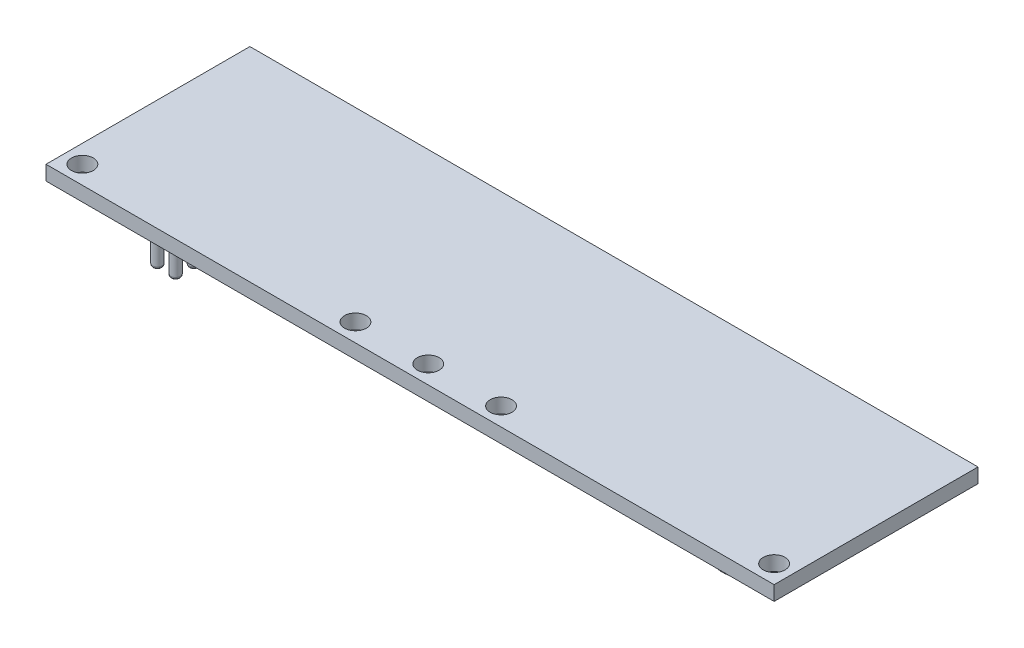
SolidWorks part; units mm, degrees
ref_plane "Front Plane" through (0, 0, 0) normal (0, 0, 1) x (1, 0, 0)
ref_plane "Top Plane" through (0, 0, 0) normal (0, 1, 0) x (1, 0, 0)
ref_plane "Right Plane" through (0, 0, 0) normal (1, 0, 0) x (0, 0, -1)
sketch "Sketch1" plane through (0, 0, 0) normal (0, 1, 0) x (1, 0, 0)
  line L0 (0, 0) -> (0, 28)
  line L1 (0, 28) -> (100, 28)
  line L2 (100, 28) -> (100, 0)
  line L3 (100, 0) -> (0, 0)
  dimension "D1" = 100
  dimension "D2" = 28
extrude "BOARD" add sketch "Sketch1" along normal blind 2
sketch "PICTURE" plane through (0, 2, 0) normal (0, 1, 0) x (1, 0, 0)
  line L0 (114.1667, 96.5) -> (570.8333, 96.5) construction
sketch "Sketch4" plane through (0, 0, 0) normal (0, 1, 0) x (1, 0, 0)
  line L0 (0, 28) -> (0, 0) construction
  line L1 (0, 0) -> (100, 0) construction
  line L2 (100, 0) -> (100, 28) construction
  circle A0 centre (2.5, 2.5) radius 1.5
  circle A1 centre (40, 2.5) radius 1.5
  circle A2 centre (50, 2.5) radius 1.5
  circle A3 centre (60, 2.5) radius 1.5
  circle A4 centre (97.5, 2.5) radius 1.5
  dimension "D1" = 3
  dimension "D4" = 10
  dimension "D6" = 10
  dimension "D2" = 2.5
  dimension "D3" = 2.5
  dimension "D5" = 37.5
  dimension "D7" = 2.5
extrude "SCREW HOLES" cut sketch "Sketch4" along normal through all and the other way through all
sketch "Sketch6" plane through (0, 0, 0) normal (0, -1, 0) x (1, 0, 0)
  line L0 (5, -7.5) -> (10, -7.5)
  line L1 (10, -7.5) -> (10, -15.5)
  line L2 (10, -15.5) -> (5, -15.5)
  line L3 (5, -15.5) -> (5, -7.5)
  line L4 (100, -28) -> (0, -28) construction
  line L5 (0, -28) -> (0, 0) construction
  dimension "D1" = 8
  dimension "D2" = 5
  dimension "D3" = 12.5
  dimension "D4" = 5
extrude "PIN BASE" add sketch "Sketch6" along normal blind 1.5 separate body
sketch "Sketch7" plane through (0, -1.5, 0) normal (0, -1, 0) x (1, 0, 0)
  line L0 (5, -7.5) -> (5, -15.5) construction
  line L1 (10, -7.5) -> (5, -7.5) construction
  circle A0 centre (6.3, -9) radius 0.65
  circle A1 centre (8.8, -9) radius 0.65
  circle A2 centre (8.8, -11.5) radius 0.65
  circle A3 centre (8.8, -14) radius 0.65
  circle A4 centre (6.3, -11.5) radius 0.65
  circle A5 centre (6.3, -14) radius 0.65
  dimension "D1" = 1.3
  dimension "D4" = 1.3
  dimension "D5" = 1.5
  dimension "D2" = 2
  dimension "D3" = 3
extrude "PINS" add sketch "Sketch7" along normal blind 10 separate body
fillet "Fillet1" radius 0.4 1 edges at (6.3, -11.5, -9.65)
fillet "Fillet2" radius 0.4 1 edges at (6.3, -11.5, -12.15)
fillet "Fillet3" radius 0.4 1 edges at (8.8, -11.5, -9.65)
fillet "Fillet4" radius 0.4 1 edges at (8.8, -11.5, -12.15)
fillet "Fillet5" radius 0.4 1 edges at (6.3, -11.5, -14.65)
fillet "Fillet6" radius 0.4 1 edges at (8.8, -11.5, -14.65)
sketch "Sketch8" plane through (0, 0, 0) normal (0, -1, 0) x (1, 0, 0)
  text T0 "GND           GND" font "Century Gothic" height in points 5
extrude "gnd" add sketch "Sketch8" along normal blind 0.1 separate body
sketch "Sketch9" plane through (0, 0, 0) normal (0, -1, 0) x (1, 0, 0)
  text T0 "5V            5V" font "Century Gothic" height in points 5
extrude "5v" add sketch "Sketch9" along normal blind 0.1 separate body
sketch "Sketch10" plane through (0, 0, 0) normal (0, -1, 0) x (1, 0, 0)
  text T0 "SCL           SDA" font "Century Gothic" height in points 5
extrude "SLC & SDA" add sketch "Sketch10" along normal blind 0.1 separate body
sketch "Sketch11" plane through (0, 0, 0) normal (0, -1, 0) x (1, 0, 0)
  line L0 (100, -28) -> (0, -28) construction
  line L1 (78, -9.5) -> (88, -9.5)
  line L2 (78, -9.5) -> (78, -19.5)
  line L3 (78, -19.5) -> (88, -19.5)
  line L4 (88, -9.5) -> (88, -19.5)
  line L5 (100, 0) -> (100, -28) construction
  dimension "D1" = 10
  dimension "D2" = 10
  dimension "D3" = 8.5
  dimension "D4" = 12
extrude "Boss-Extrude7" add sketch "Sketch11" along normal blind 5 separate body
sketch "Sketch12" plane through (0, -5, 0) normal (0, -1, 0) x (1, 0, 0)
  line L0 (83, -9.5) -> (83, -19.5) construction
  line L1 (88, -9.5) -> (78, -9.5) construction
  line L2 (78, -19.5) -> (88, -19.5) construction
  circle A0 centre (83, -14.5) radius 4.5834
extrude "Boss-Extrude8" add sketch "Sketch12" along normal blind 5
